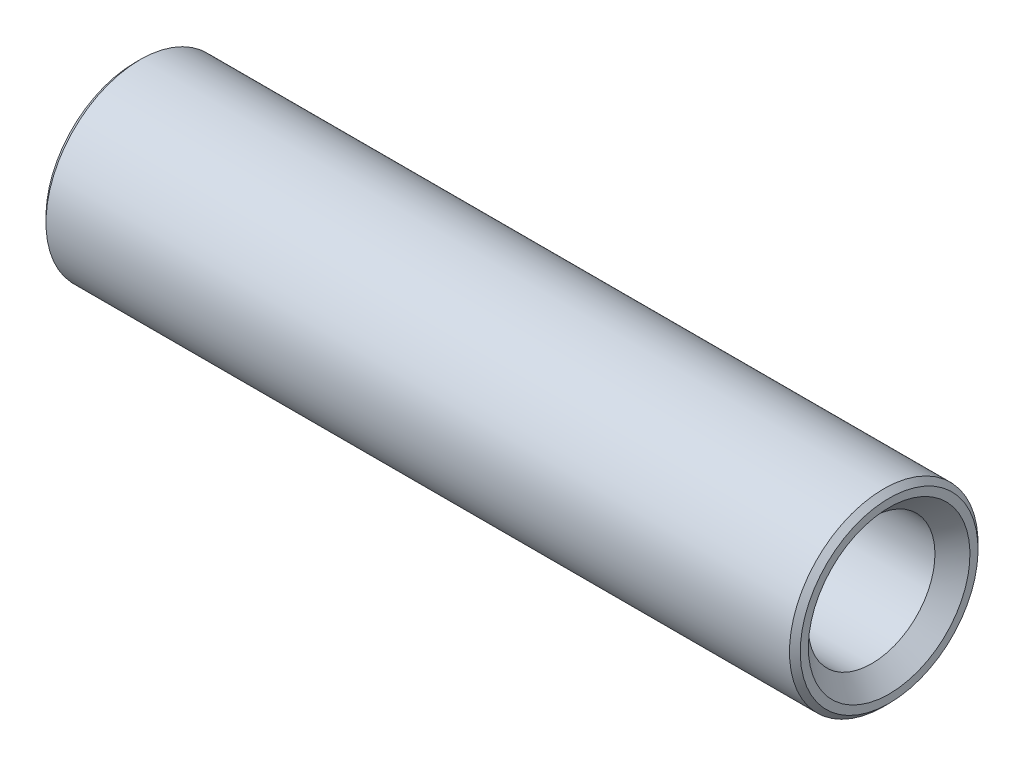
SolidWorks part; units mm, degrees
ref_plane "Front Plane" through (0, 0, 0) normal (0, 0, 1) x (1, 0, 0)
ref_plane "Top Plane" through (0, 0, 0) normal (0, 1, 0) x (1, 0, 0)
ref_plane "Right Plane" through (0, 0, 0) normal (1, 0, 0) x (0, 0, -1)
sketch "Sketch1" plane through (0, 0, 0) normal (0, 0, 1) x (1, 0, 0)
  line L0 (-14, 3) -> (-13.35, 2.35)
  line L1 (-14, 3.5) -> (14, 3.5)
  line L2 (-14, 3.5) -> (-14, 3)
  line L3 (-13.35, 2.35) -> (13.35, 2.35)
  line L4 (14, 3.5) -> (14, 3)
  line L5 (13.35, 2.35) -> (14, 3)
  line L6 (-14, 0) -> (14, 0) construction
  line L7 (0, 3.5) -> (0, 0) construction
  line L8 (-13.35, -2.35) -> (-14, -3) construction
  line L9 (13.35, -2.35) -> (14, -3) construction
  dimension "FIX_4" = 45
  dimension "FIX_2" = 0.5
  dimension "L" = 28
  dimension "FIX_6" = 45
  dimension "D" = 7
  dimension "D_s" = 4.7
revolve "Revolve1" add sketch "Sketch1" angle 360 about L6
chamfer "Chamfer1" distance 0.2 2 edges at (14, -3.5, 0) (-14, -3.5, 0)
